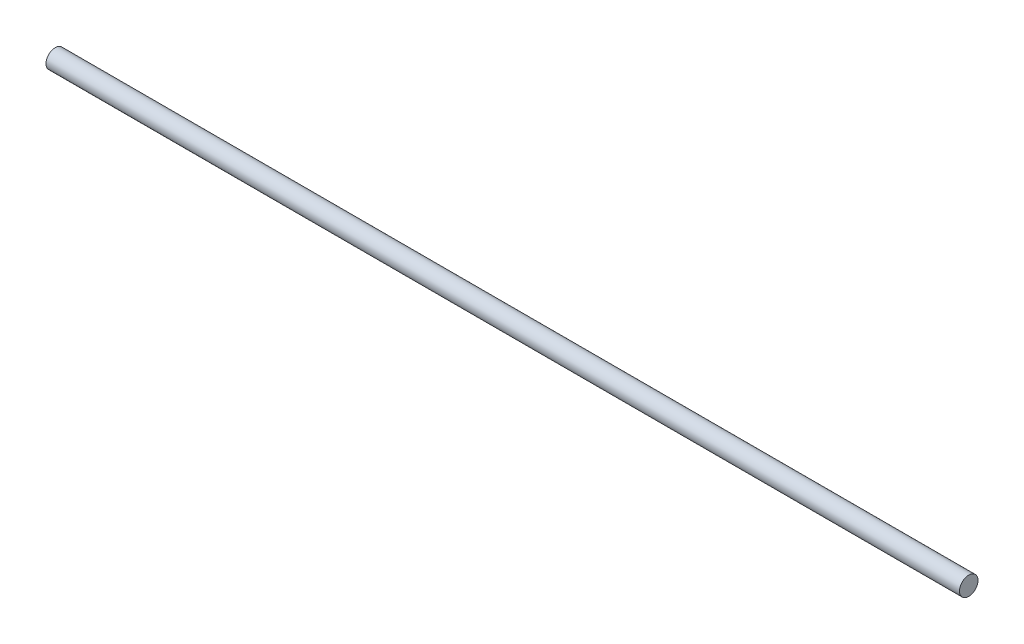
SolidWorks part; units mm, degrees
ref_plane "Спереди" through (0, 0, 0) normal (0, 0, 1) x (1, 0, 0)
ref_plane "Сверху" through (0, 0, 0) normal (0, 1, 0) x (1, 0, 0)
ref_plane "Справа" through (0, 0, 0) normal (1, 0, 0) x (0, 0, -1)
sketch "Эскиз1" plane through (0, 0, 0) normal (1, 0, 0) x (0, 0, -1)
  circle A0 centre (0, 0) radius 4.05
  dimension "D1" = 8.1
extrude "Бобышка-Вытянуть1" add sketch "Эскиз1" along normal blind 400
